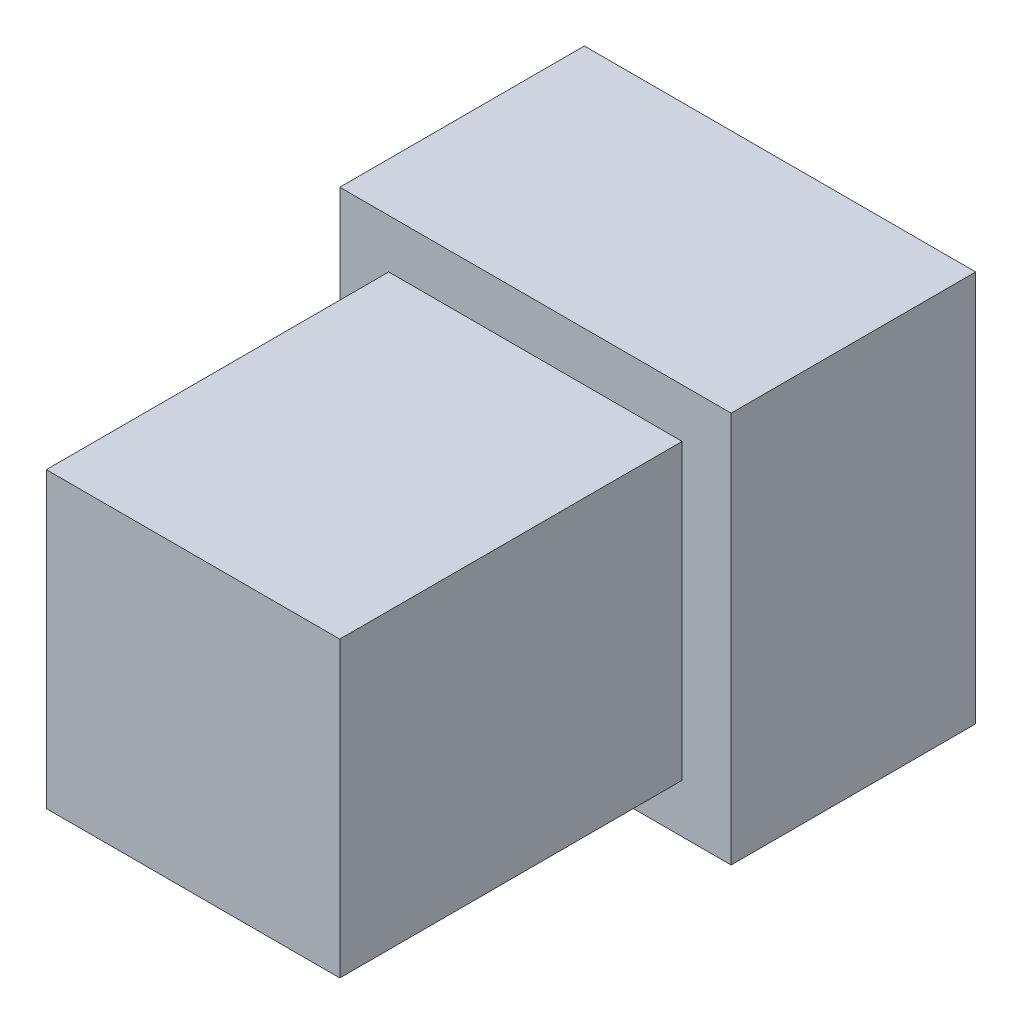
SolidWorks part; units mm, degrees
ref_plane "Front Plane" through (0, 0, 0) normal (0, 0, 1) x (1, 0, 0)
ref_plane "Top Plane" through (0, 0, 0) normal (0, 1, 0) x (1, 0, 0)
ref_plane "Right Plane" through (0, 0, 0) normal (1, 0, 0) x (0, 0, -1)
sketch "Sketch1" plane through (0, 0, 0) normal (0, 0, 1) x (1, 0, 0)
  line L1 (-4, -4) -> (4, -4)
  line L2 (-4, -4) -> (-4, 4)
  line L3 (-4, 4) -> (4, 4)
  line L4 (4, -4) -> (4, 4)
  line L5 (-4, -4) -> (4, 4) construction
  line L6 (-4, 4) -> (4, -4) construction
  point P0 (0, 0)
  dimension "D1" = 8
  dimension "D2" = 8
extrude "Boss-Extrude1" add sketch "Sketch1" along normal blind 5
sketch "Sketch3" plane through (0, 0, 5) normal (0, 0, 1) x (1, 0, 0)
  line L1 (-3, -3) -> (3, -3)
  line L2 (-3, -3) -> (-3, 3)
  line L3 (-3, 3) -> (3, 3)
  line L4 (3, -3) -> (3, 3)
  line L5 (-3, -3) -> (3, 3) construction
  line L6 (-3, 3) -> (3, -3) construction
  point P0 (0, 0)
  dimension "D1" = 6
  dimension "D2" = 6
extrude "Boss-Extrude2" add sketch "Sketch3" along normal blind 7
